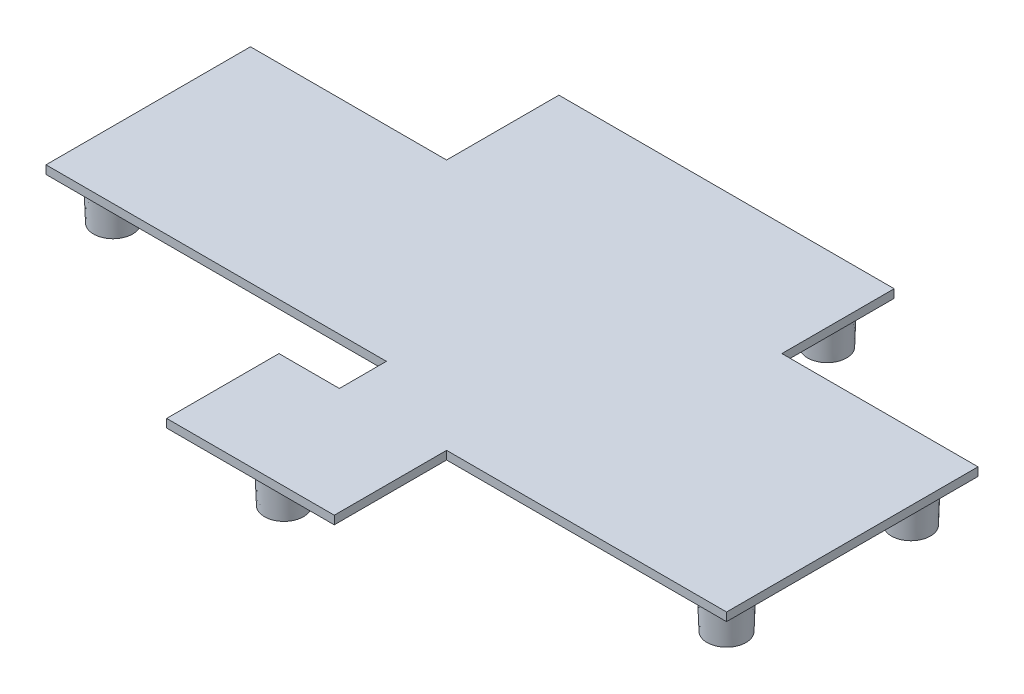
SolidWorks part; units mm, degrees
ref_plane "Front Plane" through (0, 0, 0) normal (0, 0, 1) x (1, 0, 0)
ref_plane "Top Plane" through (0, 0, 0) normal (0, 1, 0) x (1, 0, 0)
ref_plane "Right Plane" through (0, 0, 0) normal (1, 0, 0) x (0, 0, -1)
sketch "Sketch1" plane through (0, 0, 0) normal (0, 1, 0) x (1, 0, 0)
  line L0 (63.4, 30) -> (86.8, 30)
  line L1 (0, 0) -> (23.4, 0)
  line L2 (0, 0) -> (0, 30)
  line L3 (0, 30) -> (23.4, 30)
  line L4 (86.8, 0) -> (86.8, 30)
  line L6 (23.4, 30) -> (23.4, 43.4)
  line L7 (23.4, 43.4) -> (63.4, 43.4)
  line L8 (63.4, 30) -> (63.4, 43.4)
  line L10 (23.4, 0) -> (23.4, -13.4)
  line L11 (23.4, -13.4) -> (63.4, -13.4)
  line L12 (63.4, 0) -> (63.4, -13.4)
  line L13 (63.4, 0) -> (86.8, 0)
  dimension "D1" = 40
  dimension "D2" = 30
  dimension "D3" = 56.8
  dimension "D4" = 86.8
extrude "Boss-Extrude1" add sketch "Sketch1" along normal blind 1
sketch "Sketch3" plane through (0, 1, 0) normal (0, 1, 0) x (1, 0, 0)
  line L0 (23.4, -13.4) -> (63.4, -13.4) construction
  line L1 (23.4, 0) -> (33.4, 0)
  line L2 (23.4, 0) -> (23.4, -13.4)
  line L3 (23.4, -13.4) -> (33.4, -13.4)
  line L4 (33.4, 0) -> (33.4, -13.4)
  line L5 (63.4, 0) -> (86.8, 0) construction
  line L6 (63.4, -13.4) -> (53.4, -13.4)
  line L7 (63.4, -13.4) -> (63.4, 0)
  line L8 (63.4, 0) -> (53.4, 0)
  line L9 (53.4, -13.4) -> (53.4, 0)
  line L10 (23.4, 0) -> (23.4, -13.4) construction
  line L11 (0, 0) -> (23.4, 0)
  line L12 (0, 0) -> (0, 5.6063)
  line L13 (0, 5.6063) -> (40.6099, 5.6063)
  line L15 (40.6099, 5.6063) -> (40.6099, 0)
  line L16 (40.6099, 0) -> (33.4, 0)
  dimension "D1" = 10
  dimension "D2" = 10
extrude "Cut-Extrude1" cut sketch "Sketch3" against normal through all
sketch "Sketch4" plane through (0, 0, 0) normal (0, -1, 0) x (1, 0, 0)
  line L0 (13.4, -14.5) -> (73.4, -14.5)
  line L1 (13.4, -10) -> (73.4, -10)
  line L2 (13.4, -10) -> (13.4, -11.5)
  line L3 (13.4, -11.5) -> (73.4, -11.5)
  line L4 (73.4, -10) -> (73.4, -11.5)
  line L5 (13.4, -14.5) -> (13.4, -16)
  line L6 (13.4, -16) -> (73.4, -16)
  line L7 (73.4, -14.5) -> (73.4, -16)
  line L8 (13.4, -19) -> (73.4, -19)
  line L9 (13.4, -19) -> (13.4, -20.5)
  line L10 (13.4, -20.5) -> (73.4, -20.5)
  line L11 (73.4, -19) -> (73.4, -20.5)
  line L12 (13.4, -23.5) -> (73.4, -23.5)
  line L13 (13.4, -23.5) -> (13.4, -25)
  line L14 (13.4, -25) -> (73.4, -25)
  line L15 (73.4, -23.5) -> (73.4, -25)
  line L16 (43.4, -43.4) -> (43.4, 13.4) construction
  line L17 (63.4, -43.4) -> (23.4, -43.4) construction
  line L18 (33.4, 13.4) -> (53.4, 13.4) construction
  line L19 (23.4, -30) -> (0, -30) construction
  point P22 (43.4, -10)
  dimension "D2" = 1.5
  dimension "D3" = 3
  dimension "D4" = 60
  dimension "D5" = 5
  dimension "D1" = 4
extrude "Boss-Extrude3" add sketch "Sketch4" along normal blind 3
sketch "Sketch5" plane through (0, 0, 0) normal (0, -1, 0) x (-1, 0, 0)
  line L0 (0, 30) -> (0, 5.6063) construction
  line L1 (0, 5.6063) -> (-40.6099, 5.6063) construction
  line L2 (-23.4, 30) -> (0, 30) construction
  line L3 (-33.4, -13.4) -> (-53.4, -13.4) construction
  line L4 (-33.4, 0) -> (-33.4, -13.4) construction
  line L5 (-53.4, 0) -> (-86.8, 0) construction
  line L6 (-86.8, 0) -> (-86.8, 30) construction
  line L7 (-86.8, 30) -> (-63.4, 30) construction
  line L8 (-63.4, 30) -> (-63.4, 43.4) construction
  line L9 (-63.4, 43.4) -> (-23.4, 43.4) construction
  line L10 (-23.4, 43.4) -> (-23.4, 30) construction
  circle A0 centre (-4, 9.6063) radius 2.5
  circle A1 centre (-4, 26) radius 2.5
  circle A2 centre (-82.8, 26) radius 2.5
  circle A3 centre (-82.8, 4) radius 2.5
  circle A4 centre (-59.4, 39.4) radius 2.5
  circle A5 centre (-27.4, 39.4) radius 2.5
  circle A6 centre (-43.4, -9.4) radius 2.5
  point P20 (0, 0)
  point P22 (-2.9159, 33.7723)
  dimension "D1" = 5
  dimension "D2" = 4
  dimension "D3" = 4
  dimension "D4" = 4
  dimension "D5" = 4
  dimension "D6" = 4
  dimension "D7" = 10
  dimension "D8" = 4
  dimension "D9" = 4
  dimension "D10" = 4
  dimension "D11" = 4
  dimension "D12" = 4
  dimension "D13" = 4
  dimension "D14" = 4
  dimension "D15" = 4
extrude "Boss-Extrude4" add sketch "Sketch5" along normal blind 5 draft 2
